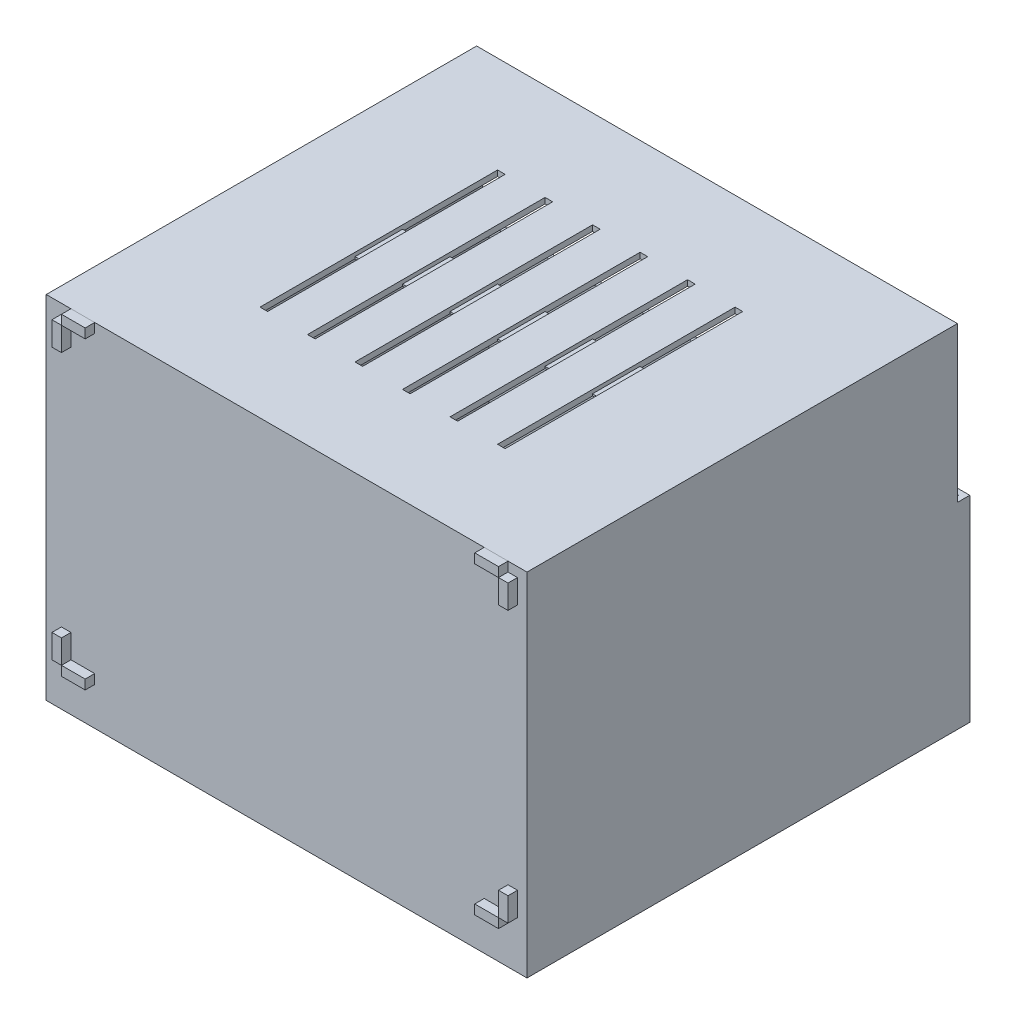
SolidWorks part; units mm, degrees
ref_plane "前视基准面" through (0, 0, 0) normal (0, 0, 1) x (1, 0, 0)
ref_plane "上视基准面" through (0, 0, 0) normal (0, 1, 0) x (1, 0, 0)
ref_plane "右视基准面" through (0, 0, 0) normal (1, 0, 0) x (0, 0, -1)
sketch "Sketch1" plane through (0, 0, 0) normal (0, 0, 1) x (1, 0, 0)
  line L1 (-9.0072, -0.0298) -> (82.9928, -0.0298)
  line L2 (-9.0072, -0.0298) -> (-9.0072, -62.0298)
  line L3 (-9.0072, -62.0298) -> (82.9928, -62.0298)
  line L4 (82.9928, -0.0298) -> (82.9928, -62.0298)
  dimension "D1" = 62
  dimension "D2" = 92
extrude "Boss-Extrude1" add sketch "Sketch1" along normal blind 2
sketch "Sketch2" plane through (0, 0, 2) normal (0, 0, 1) x (1, 0, 0)
  line L0 (82.9928, -0.0298) -> (-9.0072, -0.0298) construction
  line L1 (-11.0072, -0.0298) -> (-9.0072, -0.0298)
  line L2 (-11.0072, -0.0298) -> (-11.0072, -62.0298)
  line L3 (-11.0072, -62.0298) -> (-9.0072, -62.0298)
  line L4 (-9.0072, -0.0298) -> (-9.0072, -62.0298)
  line L5 (82.9928, -0.0298) -> (84.9928, -0.0298)
  line L6 (82.9928, -0.0298) -> (82.9928, -62.0298)
  line L7 (82.9928, -62.0298) -> (84.9928, -62.0298)
  line L8 (84.9928, -0.0298) -> (84.9928, -62.0298)
  line L9 (-9.0072, -0.0298) -> (-4.0072, -0.0298)
  line L10 (-9.0072, -0.0298) -> (-9.0072, 1.9702)
  line L11 (-9.0072, 1.9702) -> (-4.0072, 1.9702)
  line L12 (-4.0072, -0.0298) -> (-4.0072, 1.9702)
  line L13 (82.9928, -0.0298) -> (77.9928, -0.0298)
  line L14 (82.9928, -0.0298) -> (82.9928, 1.9702)
  line L15 (82.9928, 1.9702) -> (77.9928, 1.9702)
  line L16 (77.9928, -0.0298) -> (77.9928, 1.9702)
  line L17 (82.9928, -62.0298) -> (77.9928, -62.0298)
  line L18 (82.9928, -62.0298) -> (82.9928, -64.0298)
  line L19 (82.9928, -64.0298) -> (77.9928, -64.0298)
  line L20 (77.9928, -62.0298) -> (77.9928, -64.0298)
  line L21 (-9.0072, -62.0298) -> (-4.0072, -62.0298)
  line L22 (-9.0072, -62.0298) -> (-9.0072, -64.0298)
  line L23 (-9.0072, -64.0298) -> (-4.0072, -64.0298)
  line L24 (-4.0072, -62.0298) -> (-4.0072, -64.0298)
  line M20 (-9.0072, -0.0298) -> (-9.0072, -62.0298)
  line M21 (-9.0072, -62.0298) -> (82.9928, -62.0298)
  line M22 (82.9928, -62.0298) -> (82.9928, -0.0298)
  line M23 (82.9928, -0.0298) -> (-9.0072, -0.0298)
  dimension "D1" = 2
  dimension "D2" = 2
  dimension "D3" = 2
  dimension "D4" = 5
  dimension "D5" = 62
  dimension "D6" = 0
  dimension "D7" = 2
  dimension "D8" = 5
  dimension "D9" = 5
  dimension "D10" = 2
  dimension "D11" = 0
  dimension "D12" = 2
  dimension "D13" = 5
extrude "Boss-Extrude6" add sketch "Sketch2" along normal blind 2 separate body contours L12 L11 L10 M23 | L2 L3 L1 M20 | L16 L14 L15 M23 | L8 L5 L7 M22 | L20 L19 L18 M21 | L24 L22 L23 M21
sketch "Sketch4" plane through (0, 0, 2) normal (0, 0, 1) x (1, 0, 0)
  line L0 (-9.0072, -62.0298) -> (82.9928, -62.0298) construction
  line L1 (86.9928, -72.0298) -> (-13.0072, -72.0298)
  line L2 (86.9928, -72.0298) -> (86.9928, 1.9702)
  line L3 (86.9928, 1.9702) -> (-13.0072, 1.9702)
  line L4 (-13.0072, -72.0298) -> (-13.0072, 1.9702)
  line L5 (86.9928, -72.0298) -> (-13.0072, 1.9702) construction
  line L6 (86.9928, 1.9702) -> (-13.0072, -72.0298) construction
  line L9 (-11.0072, -0.0298) -> (-11.0072, -62.0298) construction
  point P0 (36.9928, -35.0298)
  dimension "D1" = 10
  dimension "D2" = 100
  dimension "D3" = 74
  dimension "D4" = 2
extrude "Boss-Extrude11" add sketch "Sketch4" against normal blind 2
sketch "Sketch5" plane through (0, 0, 0) normal (0, 0, -1) x (-1, 0, 0)
  line L0 (-86.9928, -72.0298) -> (-86.9928, 1.9702) construction
  line L1 (-86.9928, -70.8298) -> (13.0072, -70.8298)
  line L2 (-86.9928, -70.8298) -> (-86.9928, -72.0298)
  line L3 (-86.9928, -72.0298) -> (13.0072, -72.0298)
  line L4 (13.0072, -70.8298) -> (13.0072, -72.0298)
  dimension "D1" = 1.2
extrude "Boss-Extrude12" add sketch "Sketch5" along normal blind 90
sketch "Sketch6" plane through (-13.0072, 0, 0) normal (-1, 0, 0) x (0, 0, 1)
  line L0 (0, 1.9702) -> (2, 1.9702) construction
  line L1 (2, -72.0298) -> (-90, -72.0298)
  line L2 (2, -72.0298) -> (2, 1.9702)
  line L3 (2, 1.9702) -> (-90, 1.9702)
  line L4 (-90, -72.0298) -> (-90, 1.9702)
  line L5 (-90, -72.0298) -> (-90, -70.8298) construction
extrude "Boss-Extrude13" add sketch "Sketch6" along normal blind 1.2
sketch "Sketch7" plane through (0, 0, 2) normal (0, 0, 1) x (1, 0, 0)
  line L0 (86.9928, 1.9702) -> (-14.2072, 1.9702) construction
  point P0 (36.3928, 1.9702)
ref_plane "Plane1" through (36.3928, 0, 0) normal (1, 0, 0) x (0, 0, -1)
mirror "Mirror1" about plane through (36.3928, 0, 0) normal (1, 0, 0) of "Boss-Extrude13"
sketch "Sketch8" plane through (0, 0, -90) normal (0, 0, -1) x (-1, 0, 0)
  line L1 (-86.9928, 1.9702) -> (14.2072, 1.9702)
  line L2 (-86.9928, 1.9702) -> (-86.9928, -72.0298)
  line L3 (-86.9928, -72.0298) -> (14.2072, -72.0298)
  line L4 (14.2072, 1.9702) -> (14.2072, -72.0298)
extrude "Boss-Extrude14" add sketch "Sketch8" along normal blind 1.2
sketch "Sketch10" plane through (0, -72.0298, 0) normal (0, -1, 0) x (1, 0, 0)
  line L3 (5.5928, -18.2) -> (7.1928, -18.2)
  line L4 (5.5928, -18.2) -> (5.5928, -68.2)
  line L5 (5.5928, -68.2) -> (7.1928, -68.2)
  line L6 (7.1928, -18.2) -> (7.1928, -68.2)
  line L7 (-14.2072, -91.2) -> (-14.2072, 2) construction
  line L8 (86.9928, -91.2) -> (-14.2072, -91.2) construction
  line L9 (15.5928, -18.2) -> (15.5928, -68.2)
  line L10 (15.5928, -18.2) -> (17.1928, -18.2)
  line L11 (17.1928, -18.2) -> (17.1928, -68.2)
  line L12 (15.5928, -68.2) -> (17.1928, -68.2)
  line L13 (25.5928, -18.2) -> (25.5928, -68.2)
  line L14 (25.5928, -18.2) -> (27.1928, -18.2)
  line L15 (27.1928, -18.2) -> (27.1928, -68.2)
  line L16 (25.5928, -68.2) -> (27.1928, -68.2)
  line L17 (35.5928, -18.2) -> (35.5928, -68.2)
  line L18 (35.5928, -18.2) -> (37.1928, -18.2)
  line L19 (37.1928, -18.2) -> (37.1928, -68.2)
  line L20 (35.5928, -68.2) -> (37.1928, -68.2)
  line L21 (45.5928, -18.2) -> (45.5928, -68.2)
  line L22 (45.5928, -18.2) -> (47.1928, -18.2)
  line L23 (47.1928, -18.2) -> (47.1928, -68.2)
  line L24 (45.5928, -68.2) -> (47.1928, -68.2)
  line L25 (55.5928, -18.2) -> (55.5928, -68.2)
  line L26 (55.5928, -18.2) -> (57.1928, -18.2)
  line L27 (57.1928, -18.2) -> (57.1928, -68.2)
  line L28 (55.5928, -68.2) -> (57.1928, -68.2)
  line L29 (65.5928, -18.2) -> (65.5928, -68.2)
  line L30 (65.5928, -18.2) -> (67.1928, -18.2)
  line L31 (67.1928, -18.2) -> (67.1928, -68.2)
  line L32 (65.5928, -68.2) -> (67.1928, -68.2)
  line L34 (86.9928, -91.2) -> (86.9928, 2) construction
  dimension "D1" = 1.6
  dimension "D2" = 50
  dimension "D3" = 19.8
  dimension "D4" = 23
  dimension "D6" = 19.8
  dimension "D5" = 7
extrude "Cut-Extrude1" cut sketch "Sketch10" against normal blind 105
sketch "Sketch11" plane through (0, -72.0298, 0) normal (0, -1, 0) x (1, 0, 0)
  line L0 (65.5928, -18.2) -> (65.5928, -68.2) construction
  line L1 (60.5928, -18.2) -> (62.1928, -18.2)
  line L2 (60.5928, -18.2) -> (60.5928, -38.2)
  line L3 (60.5928, -38.2) -> (62.1928, -38.2)
  line L4 (62.1928, -18.2) -> (62.1928, -38.2)
  line L7 (67.1928, -18.2) -> (65.5928, -18.2) construction
  line L9 (65.5928, -68.2) -> (67.1928, -68.2) construction
  line L10 (50.5928, -18.2) -> (50.5928, -38.2)
  line L11 (50.5928, -18.2) -> (52.1928, -18.2)
  line L12 (52.1928, -18.2) -> (52.1928, -38.2)
  line L13 (50.5928, -38.2) -> (52.1928, -38.2)
  line L14 (40.5928, -18.2) -> (40.5928, -38.2)
  line L15 (40.5928, -18.2) -> (42.1928, -18.2)
  line L16 (42.1928, -18.2) -> (42.1928, -38.2)
  line L17 (40.5928, -38.2) -> (42.1928, -38.2)
  line L18 (30.5928, -18.2) -> (30.5928, -38.2)
  line L19 (30.5928, -18.2) -> (32.1928, -18.2)
  line L20 (32.1928, -18.2) -> (32.1928, -38.2)
  line L21 (30.5928, -38.2) -> (32.1928, -38.2)
  line L22 (20.5928, -18.2) -> (20.5928, -38.2)
  line L23 (20.5928, -18.2) -> (22.1928, -18.2)
  line L24 (22.1928, -18.2) -> (22.1928, -38.2)
  line L25 (20.5928, -38.2) -> (22.1928, -38.2)
  line L26 (10.5928, -18.2) -> (10.5928, -38.2)
  line L27 (10.5928, -18.2) -> (12.1928, -18.2)
  line L28 (12.1928, -18.2) -> (12.1928, -38.2)
  line L29 (10.5928, -38.2) -> (12.1928, -38.2)
  line L30 (50.5928, -48.2) -> (50.5928, -68.2)
  line L31 (50.5928, -48.2) -> (52.1928, -48.2)
  line L32 (52.1928, -48.2) -> (52.1928, -68.2)
  line L33 (50.5928, -68.2) -> (52.1928, -68.2)
  line L34 (40.5928, -48.2) -> (40.5928, -68.2)
  line L35 (40.5928, -48.2) -> (42.1928, -48.2)
  line L36 (42.1928, -48.2) -> (42.1928, -68.2)
  line L37 (40.5928, -68.2) -> (42.1928, -68.2)
  line L38 (30.5928, -48.2) -> (30.5928, -68.2)
  line L39 (30.5928, -48.2) -> (32.1928, -48.2)
  line L40 (32.1928, -48.2) -> (32.1928, -68.2)
  line L41 (30.5928, -68.2) -> (32.1928, -68.2)
  line L42 (20.5928, -48.2) -> (20.5928, -68.2)
  line L43 (20.5928, -48.2) -> (22.1928, -48.2)
  line L44 (22.1928, -48.2) -> (22.1928, -68.2)
  line L45 (20.5928, -68.2) -> (22.1928, -68.2)
  line L46 (10.5928, -48.2) -> (10.5928, -68.2)
  line L47 (10.5928, -48.2) -> (12.1928, -48.2)
  line L48 (12.1928, -48.2) -> (12.1928, -68.2)
  line L49 (10.5928, -68.2) -> (12.1928, -68.2)
  line L50 (60.5928, -48.2) -> (60.5928, -68.2)
  line L51 (60.5928, -48.2) -> (62.1928, -48.2)
  line L52 (62.1928, -48.2) -> (62.1928, -68.2)
  line L53 (60.5928, -68.2) -> (62.1928, -68.2)
  line L54 (7.1928, -68.2) -> (7.1928, -18.2) construction
  dimension "D1" = 3.4
  dimension "D2" = 1.6
  dimension "D3" = 0
  dimension "D4" = 30
  dimension "D7" = 3.4
  dimension "D8" = 3.4
  dimension "D9" = 10
  dimension "D5" = 6
  dimension "D6" = 2
extrude "Cut-Extrude2" cut sketch "Sketch11" against normal blind 10
sketch "Sketch12" plane through (0, -72.0298, 0) normal (0, -1, 0) x (1, 0, 0)
  line L0 (12.1928, -48.2) -> (10.5928, -48.2) construction
  line L1 (10.5928, -38.2) -> (12.1928, -38.2)
  line L2 (10.5928, -38.2) -> (10.5928, -48.2)
  line L3 (10.5928, -48.2) -> (12.1928, -48.2)
  line L4 (12.1928, -38.2) -> (12.1928, -48.2)
  line L5 (15.5928, -18.2) -> (15.5928, -68.2) construction
  line L6 (15.5928, -18.2) -> (15.5928, -68.2)
  line L7 (20.5928, -38.2) -> (20.5928, -48.2)
  line L8 (20.5928, -38.2) -> (22.1928, -38.2)
  line L9 (22.1928, -38.2) -> (22.1928, -48.2)
  line L10 (20.5928, -48.2) -> (22.1928, -48.2)
  line L11 (30.5928, -38.2) -> (30.5928, -48.2)
  line L12 (30.5928, -38.2) -> (32.1928, -38.2)
  line L13 (32.1928, -38.2) -> (32.1928, -48.2)
  line L14 (30.5928, -48.2) -> (32.1928, -48.2)
  line L15 (40.5928, -38.2) -> (40.5928, -48.2)
  line L16 (40.5928, -38.2) -> (42.1928, -38.2)
  line L17 (42.1928, -38.2) -> (42.1928, -48.2)
  line L18 (40.5928, -48.2) -> (42.1928, -48.2)
  line L19 (50.5928, -38.2) -> (50.5928, -48.2)
  line L20 (50.5928, -38.2) -> (52.1928, -38.2)
  line L21 (52.1928, -38.2) -> (52.1928, -48.2)
  line L22 (50.5928, -48.2) -> (52.1928, -48.2)
  line L23 (60.5928, -38.2) -> (60.5928, -48.2)
  line L24 (60.5928, -38.2) -> (62.1928, -38.2)
  line L25 (62.1928, -38.2) -> (62.1928, -48.2)
  line L26 (60.5928, -48.2) -> (62.1928, -48.2)
  dimension "D1" = 1.6
  dimension "D2" = 6
extrude "Cut-Extrude3" cut sketch "Sketch12" against normal blind 0.8 contours L23 L26 L25 L24 | L15 L18 L17 L16 | L4 L1 L2 L3 | L21 L22 L19 L20 | L13 L14 L11 L12 | L9 L10 L7 L8
sketch "Sketch14" plane through (0, 0, 4) normal (0, 0, 1) x (1, 0, 0)
  line L0 (-11.0072, -0.0298) -> (-11.0072, -62.0298) construction
  line L1 (-11.0072, -5.0298) -> (-9.0072, -5.0298)
  line L2 (-11.0072, -5.0298) -> (-11.0072, -57.0298)
  line L3 (-11.0072, -57.0298) -> (-9.0072, -57.0298)
  line L4 (-9.0072, -5.0298) -> (-9.0072, -57.0298)
  line L5 (-9.0072, -0.0298) -> (-9.0072, -62.0298) construction
  line L6 (82.9928, -5.0298) -> (82.9928, -57.0298)
  line L7 (-11.0072, -0.0298) -> (-9.0072, -0.0298) construction
  line L8 (-11.0072, -62.0298) -> (-9.0072, -62.0298) construction
  line L9 (82.9928, -5.0298) -> (84.9928, -5.0298)
  line L10 (84.9928, -5.0298) -> (84.9928, -57.0298)
  line L11 (82.9928, -57.0298) -> (84.9928, -57.0298)
  line L12 (84.9928, -0.0298) -> (84.9928, -62.0298) construction
  dimension "D1" = 5
  dimension "D2" = 5
  dimension "D4" = 0
  dimension "D3" = 2
extrude "Cut-Extrude4" cut sketch "Sketch14" against normal up to surface (2 mm away) up to face at (36.3928, -35.0298, 2)
sketch "Sketch15" plane through (-13.0072, 0, 0) normal (1, 0, 0) x (0, 0, -1)
  line L0 (0, 1.9702) -> (0, -70.8298) construction
  line L1 (0, -28.0298) -> (91.2, -28.0298)
  line L2 (0, -28.0298) -> (0, -30.6298)
  line L3 (0, -30.6298) -> (91.2, -30.6298)
  line L4 (91.2, -28.0298) -> (91.2, -30.6298)
  line L7 (0, 1.9702) -> (90, 1.9702) construction
  line L8 (91.2, 1.9702) -> (91.2, -72.0298) construction
  dimension "D1" = 2.6
  dimension "D2" = 30
  dimension "D3" = 0
extrude "Cut-Extrude5" cut sketch "Sketch15" against normal blind 0.8
mirror "Mirror2" about plane through (36.3928, 0, 0) normal (1, 0, 0) of "Cut-Extrude5"
sketch "Sketch16" plane through (0, 1.9702, 0) normal (0, 1, 0) x (1, 0, 0)
  line L0 (-14.2072, 91.2) -> (86.9928, 91.2) construction
  line L1 (-13.0072, 90) -> (85.7928, 90)
  line L2 (-13.0072, 90) -> (-13.0072, 91.2)
  line L3 (-13.0072, 91.2) -> (85.7928, 91.2)
  line L4 (85.7928, 90) -> (85.7928, 91.2)
extrude "Cut-Extrude7" cut sketch "Sketch16" against normal up to surface (32.6 mm away) up to face at (-13.3272, -30.6298, -54.48)
sketch "Sketch17" plane through (0, -72.0298, 0) normal (0, -1, 0) x (1, 0, 0)
  line L0 (-14.2072, -91.2) -> (-14.2072, 2) construction
  line L1 (-7.2072, -16) -> (0.7928, -16)
  line L2 (-7.2072, -16) -> (-7.2072, -71)
  line L3 (-7.2072, -71) -> (0.7928, -71)
  line L4 (0.7928, -16) -> (0.7928, -71)
  line L5 (-14.2072, 2) -> (86.9928, 2) construction
  dimension "D1" = 7
  dimension "D2" = 8
  dimension "D3" = 18
  dimension "D4" = 55
extrude "Boss-Extrude15" add sketch "Sketch17" along normal blind 2
mirror "Mirror3" about plane through (36.3928, 0, 0) normal (1, 0, 0) of "Boss-Extrude15"
sketch "Sketch18" plane through (0, -30.6298, 0) normal (0, 1, 0) x (1, 0, 0)
  line L8 (-13.0072, 0) -> (-13.0072, 90)
  line L9 (-13.0072, 90) -> (85.7928, 90)
  line L10 (85.7928, 90) -> (85.7928, 0)
  line L11 (85.7928, 0) -> (86.5928, 0)
  line L12 (86.5928, 0) -> (86.5928, 91.2)
  line L13 (86.5928, 91.2) -> (-13.8072, 91.2)
  line L14 (-13.8072, 91.2) -> (-13.8072, 0)
  line L15 (-13.8072, 0) -> (-13.0072, 0)
  line L16 (-13.0072, 0) -> (-13.0072, 90)
  line L17 (-13.0072, 90) -> (85.7928, 90)
  line L18 (85.7928, 90) -> (85.7928, 0)
  line L19 (85.7928, 0) -> (86.5928, 0)
  line L20 (86.5928, 0) -> (86.5928, 91.2)
  line L21 (86.5928, 91.2) -> (-13.8072, 91.2)
  line L22 (-13.8072, 91.2) -> (-13.8072, 0)
  line L23 (-13.8072, 0) -> (-13.0072, 0)
  dimension "D1" = 0
sketch "Sketch20" plane through (85.7928, 0, 0) normal (-1, 0, 0) x (0, 0, 1)
  line L0 (0, -28.0298) -> (0, 1.9702) construction
  line L1 (-88.6, 1.9702) -> (0, 1.9702)
  line L2 (-88.6, 1.9702) -> (-88.6, 0.7702)
  line L3 (-88.6, 0.7702) -> (0, 0.7702)
  line L4 (0, 1.9702) -> (0, 0.7702)
  line L5 (-91.2, -28.0298) -> (-91.2, 1.9702) construction
  line L6 (0, 1.9702) -> (-91.2, 1.9702) construction
  dimension "D1" = 1.2
  dimension "D2" = 2.6
  dimension "D3" = 1.2
extrude "Boss-Extrude16" add sketch "Sketch20" along normal up to next (98.8 mm away)
sketch "Sketch21" plane through (0, 1.9702, 0) normal (0, 1, 0) x (1, 0, 0)
  line L0 (86.9928, 91.2) -> (86.9928, -2) construction
  line L1 (-14.2072, 91.2) -> (-13.0072, 91.2)
  line L2 (-14.2072, 91.2) -> (-14.2072, 88.6)
  line L3 (-14.2072, 88.6) -> (-13.0072, 88.6)
  line L4 (-13.0072, 91.2) -> (-13.0072, 88.6)
  line L5 (85.7928, 91.2) -> (86.9928, 91.2)
  line L6 (85.7928, 91.2) -> (85.7928, 88.6)
  line L7 (85.7928, 88.6) -> (86.9928, 88.6)
  line L8 (86.9928, 91.2) -> (86.9928, 88.6)
extrude "Cut-Extrude8" cut sketch "Sketch21" against normal up to surface (32.6 mm away) up to face at (36.3928, -30.6298, -45.3)
sketch "Sketch28" plane through (0, -72.0298, 0) normal (0, -1, 0) x (1, 0, 0)
  line L0 (-14.2072, 2) -> (86.9928, 2) construction
  line L2 (86.9928, -91.2) -> (86.9928, 2) construction
  point P0 (67.1928, -18.2)
  point P1 (67.1928, 2)
  point P3 (67.1928, -68.2)
  point P8 (86.9928, -68.2)
  dimension "D1" = 19.8
  dimension "D2" = 20.2
ref_plane "Plane2" through (0, -35.0298, 0) normal (0, 1, 0) x (1, 0, 0)
mirror "Mirror4" about plane through (0, -35.0298, 0) normal (0, 1, 0) of "Cut-Extrude2"
mirror "Mirror5" about plane through (0, -35.0298, 0) normal (0, 1, 0) of "Cut-Extrude3"
